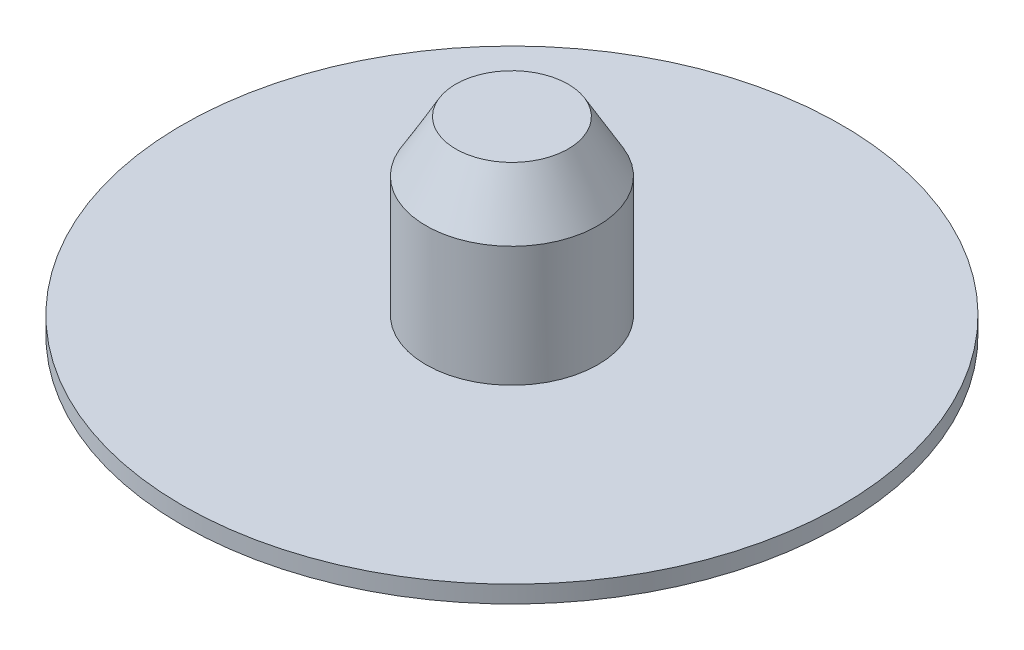
SolidWorks part; units mm, degrees
ref_plane "Front Plane" through (0, 0, 0) normal (0, 0, 1) x (1, 0, 0)
ref_plane "Top Plane" through (0, 0, 0) normal (0, 1, 0) x (1, 0, 0)
ref_plane "Right Plane" through (0, 0, 0) normal (1, 0, 0) x (0, 0, -1)
sketch "Sketch1" plane through (0, 0, 0) normal (0, 1, 0) x (1, 0, 0)
  circle A0 centre (0, 0) radius 5.75
extrude "Boss-Extrude1" add sketch "Sketch1" along normal blind 0.3
sketch "Sketch2" plane through (0, 0.3, 0) normal (0, 1, 0) x (1, 0, 0)
  circle A0 centre (0, 0) radius 1.5
extrude "Boss-Extrude2" add sketch "Sketch2" along normal blind 3
chamfer "Chamfer1" distance 0.9 angle 30 1 edges at (0, 3.3, 1.5)
